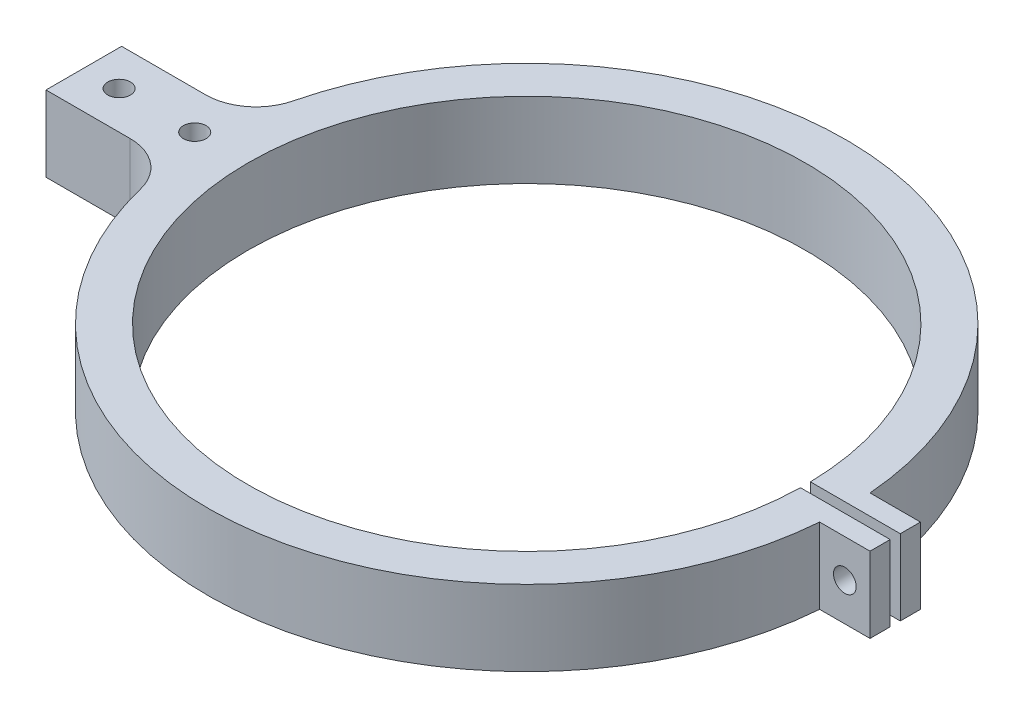
SolidWorks part; units mm, degrees
ref_plane "Front Plane" through (0, 0, 0) normal (0, 0, 1) x (1, 0, 0)
ref_plane "Top Plane" through (0, 0, 0) normal (0, 1, 0) x (1, 0, 0)
ref_plane "Right Plane" through (0, 0, 0) normal (1, 0, 0) x (0, 0, -1)
sketch "Sketch1" plane through (0, 0, 0) normal (0, 1, 0) x (1, 0, 0)
  line L0 (0, 0) -> (-115.2506, 0) construction
  line L1 (46.2029, 0) -> (74.7803, 0) construction
  line L2 (-87.8541, -7.5) -> (-62.8541, -7.5)
  line L3 (-87.8541, -7.5) -> (-87.8541, 7.5)
  line L4 (-87.8541, 7.5) -> (-62.8541, 7.5)
  line L6 (-87.8541, -7.5) -> (-62.8541, 7.5) construction
  line L7 (-87.8541, 7.5) -> (-62.8541, -7.5) construction
  line L8 (55.291, 1) -> (73.1022, 1)
  line L9 (73.1022, 1) -> (73.1022, 5)
  line L10 (73.1022, 5) -> (63.1022, 5)
  line L11 (73.1022, -5) -> (63.1022, -5)
  line L12 (73.1022, -1) -> (73.1022, -5)
  line L13 (55.291, -1) -> (73.1022, -1)
  arc A0 (55.291, 1) -> (55.291, -1) centre (0, 0) ccw
  arc A1 (63.1022, 5) -> (-62.8541, 7.5) centre (0, 0) ccw
  circle A2 centre (0, 0) radius 55.3 construction
  circle A3 centre (0, 0) radius 63.3 construction
  arc A4 (-62.8541, -7.5) -> (63.1022, -5) centre (0, 0) ccw
  circle A5 centre (-80.8541, 0) radius 2.25
  circle A6 centre (-65.8541, 0) radius 2.25
  point P5 (-75.3541, 0)
  dimension "D1" = 110.6
  dimension "D8" = 4.5
  dimension "D9" = 4.5
  dimension "D3" = 25
  dimension "D4" = 15
  dimension "D5" = 2
  dimension "D6" = 4
  dimension "D7" = 10
  dimension "D10" = 15
  dimension "D11" = 7
  dimension "D2" = 8
extrude "Boss-Extrude1" add sketch "Sketch1" along normal blind 15
sketch "Sketch2" plane through (0, 0, 5) normal (0, 0, 1) x (1, 0, 0)
  line L0 (73.1022, 7.5) -> (63.1022, 7.5) construction
  line L1 (73.1022, 15) -> (73.1022, 0) construction
  line L2 (63.1022, 15) -> (63.1022, 0) construction
  circle A0 centre (68.1022, 7.5) radius 2.25
  dimension "D1" = 4.5
extrude "Cut-Extrude1" cut sketch "Sketch2" against normal blind 20
fillet "Fillet1" radius 10 2 edges at (-62.8541, 7.5, -7.5) (-62.8541, 7.5, 7.5)
